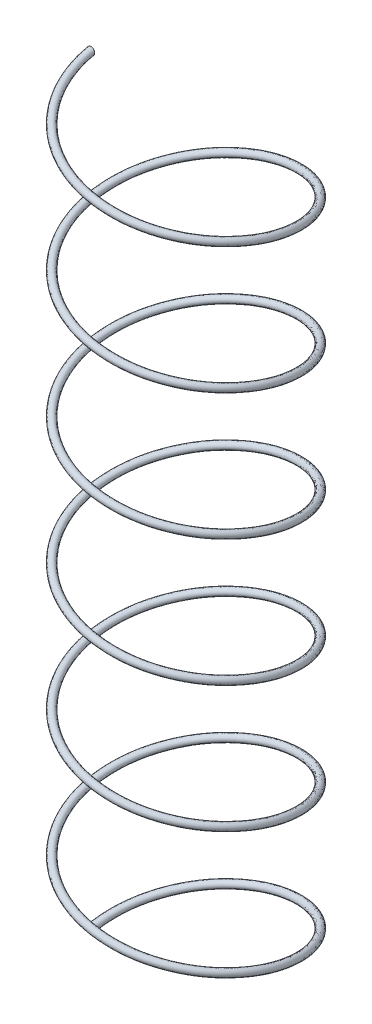
SolidWorks part; units mm, degrees
material "AISI 316 Stainless Steel Sheet (SS)"
ref_plane "Front Plane" through (0, 0, 0) normal (0, 0, 1) x (1, 0, 0)
ref_plane "Top Plane" through (0, 0, 0) normal (0, 1, 0) x (1, 0, 0)
ref_plane "Right Plane" through (0, 0, 0) normal (1, 0, 0) x (0, 0, -1)
sketch "Sketch1" plane through (0, 0, 0) normal (0, 1, 0) x (1, 0, 0)
  circle A0 centre (0, 0) radius 3.75
  dimension "D1" = 7.5
curve "Helix/Spiral1" pitch 5 height 30 turns 6
sketch "Sketch2" plane through (0, 0, 0) normal (0, 0, 1) x (1, 0, 0)
  circle A0 centre (-3.7493, 0) radius 0.1473
sweep "Sweep1" add profiles "Sketch2" path "Helix/Spiral1"
sketch "Sketch3" plane through (0, 0, 0) normal (0, 0, 1) x (1, 0, 0)
  line L0 (0, 31.9351) -> (0, -4.5504) construction
